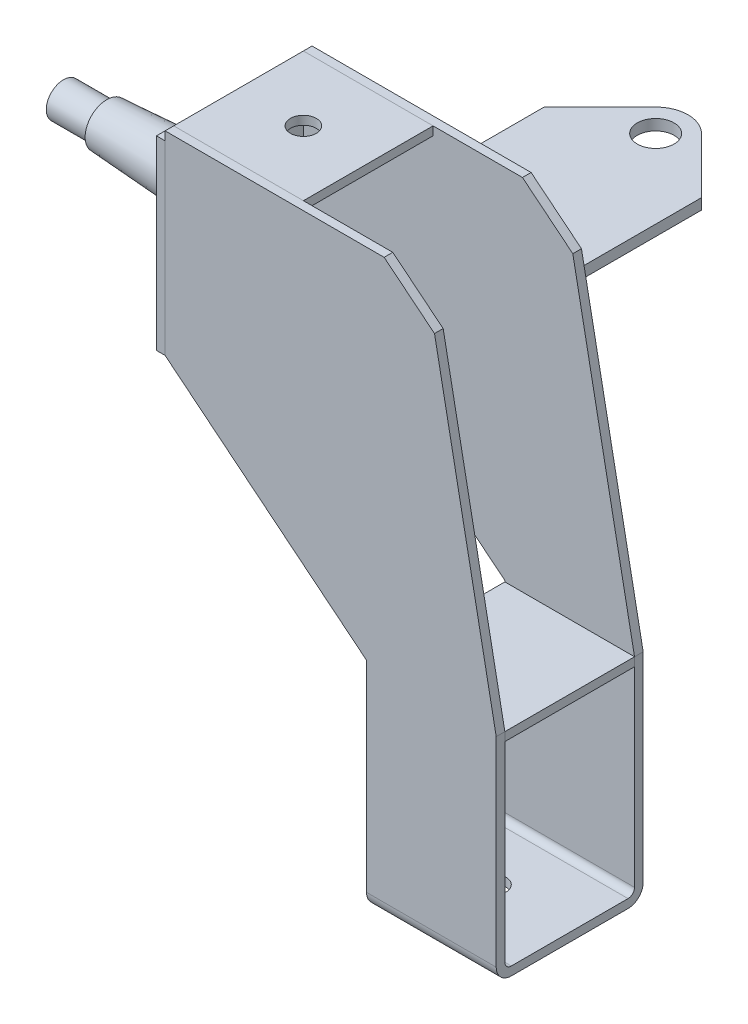
SolidWorks part; units mm, degrees
ref_plane "Front Plane" through (0, 0, 0) normal (0, 0, 1) x (1, 0, 0)
ref_plane "Top Plane" through (0, 0, 0) normal (0, 1, 0) x (1, 0, 0)
ref_plane "Right Plane" through (0, 0, 0) normal (1, 0, 0) x (0, 0, -1)
sketch "Sketch1" plane through (0, 0, 0) normal (0, 0, 1) x (1, 0, 0)
  line L0 (0, 0) -> (0, -100)
  line L1 (0, -2.2) -> (0, 2.2) construction
  line L2 (0, 0) -> (93.2275, 75.5556)
  line L3 (93.2275, 75.5556) -> (93.2275, 165.5556)
  line L4 (0, -100) -> (-60, -100)
  line L5 (-60, -100) -> (-60, -0.5906)
  line L6 (-60, -0.5906) -> (-31.4466, 146.6667)
  line L7 (-31.4466, 146.6667) -> (-8.1397, 165.5556)
  line L8 (-8.1397, 165.5556) -> (93.2275, 165.5556)
  point P0 (0, 0)
  dimension "D1" = 100
  dimension "D2" = 120
  dimension "D3" = 90
  dimension "D4" = 60
  dimension "D5" = 90
  dimension "D6" = 30
  dimension "D7" = 150
  dimension "D8" = 150
  dimension "D9" = 190
  dimension "D10" = 101.3672
  dimension "D11" = 129.023
  dimension "D12" = 99.4094
sketch "Sketch3" plane through (0, 0, 0) normal (1, 0, 0) x (0, 0, -1)
  line L2 (93.1124, 165.5556) -> (89.1124, 165.5556)
  line L3 (89.1124, 165.5556) -> (89.1124, -93)
  line L4 (86.1124, -96) -> (32.1124, -96)
  line L5 (0, 146.6667) -> (0, 165.5556) construction
  line L6 (0, 75.5556) -> (0, 165.5556) construction
  line L7 (0, -100) -> (0, -0.5906) construction
  line L8 (0, 84.2751) -> (0, -84.2751) construction
  line L9 (29.1124, -93) -> (29.1124, 165.5556)
  line L10 (29.1124, 165.5556) -> (25.1124, 165.5556)
  line L12 (93.1124, 161.5556) -> (93.1124, 161.5556)
  line L13 (93.1124, 165.5556) -> (93.1124, -93)
  line L14 (86.1124, -100) -> (32.1124, -100)
  line L15 (25.1124, -93) -> (25.1124, 168.1451)
  line L16 (25.1124, 161.5556) -> (25.1124, 161.5556)
  line L17 (93.1124, 161.5556) -> (93.1124, -93) construction
  line L18 (25.1124, -93) -> (25.1124, 161.5556) construction
  arc A0 (32.1124, -96) -> (29.1124, -93) centre (32.1124, -93) cw
  arc A1 (89.1124, -93) -> (86.1124, -96) centre (86.1124, -93) cw
  arc A2 (93.1124, -93) -> (86.1124, -100) centre (86.1124, -93) cw
  arc A3 (32.1124, -100) -> (25.1124, -93) centre (32.1124, -93) cw
  point P2 (0, 165.5556)
  point P7 (0, -100)
  point P20 (29.1124, -96)
  point P23 (89.1124, -96)
  dimension "D6" = 3
  dimension "D1" = 4
  dimension "D5" = 60
extrude "Boss-Extrude2" add sketch "Sketch3" along normal mid plane 214 contours A3 L14 A2 L13 L2 L3 A1 L4 A0 L9 L10 L15
sketch "Sketch4" plane through (0, 0, 0) normal (0, 0, 1) x (1, 0, 0)
  line L8 (-190, 11.8967) -> (-190, -230)
  line L9 (-190, -230) -> (130, -230)
  line L10 (130, -230) -> (130, -61.9751)
  line L11 (130, -61.9751) -> (223.2275, 13.5805)
  line L12 (223.2275, 13.5805) -> (223.2275, 295.5556)
  line L13 (223.2275, 295.5556) -> (-54.2043, 295.5556)
  line L14 (-54.2043, 295.5556) -> (-150.0618, 217.8685)
  line L15 (-150.0618, 217.8685) -> (-190, 11.8967)
  line L16 (-60, -0.5906) -> (-60, -100)
  line L17 (-60, -100) -> (0, -100)
  line L18 (0, -100) -> (0, 0)
  line L19 (0, 0) -> (93.2275, 75.5556)
  line L20 (93.2275, 75.5556) -> (93.2275, 165.5556)
  line L21 (93.2275, 165.5556) -> (-8.1397, 165.5556)
  line L22 (-8.1397, 165.5556) -> (-31.4466, 146.6667)
  line L23 (-31.4466, 146.6667) -> (-60, -0.5906)
  line L24 (-60, -0.5906) -> (-60, -100)
  line L25 (-60, -100) -> (0, -100)
  line L26 (0, -100) -> (0, 0)
  line L27 (0, 0) -> (93.2275, 75.5556)
  line L28 (93.2275, 75.5556) -> (93.2275, 165.5556)
  line L29 (93.2275, 165.5556) -> (-8.1397, 165.5556)
  line L30 (-8.1397, 165.5556) -> (-31.4466, 146.6667)
  line L31 (-31.4466, 146.6667) -> (-60, -0.5906)
  dimension "D1" = 0
  dimension "D2" = 130
extrude "Cut-Extrude1" cut sketch "Sketch4" against normal blind 214
sketch "Sketch5" plane through (0, 0, 0) normal (1, 0, 0) x (0, 0, -1)
  line L0 (89.1124, 0) -> (89.1124, -93) construction
  line L1 (29.1124, -0.5906) -> (89.1124, -0.5906)
  line L2 (29.1124, -0.5906) -> (29.1124, -4.5906)
  line L3 (29.1124, -4.5906) -> (89.1124, -4.5906)
  line L4 (89.1124, -0.5906) -> (89.1124, -4.5906)
  dimension "D1" = 4
  dimension "D2" = 60
extrude "Boss-Extrude3" add sketch "Sketch5" against normal blind 60 separate body
sketch "Sketch6" plane through (93.2275, 0, 0) normal (1, 0, 0) x (0, 0, -1)
  line L0 (89.1124, 165.5556) -> (89.1124, 75.5556) construction
  line L1 (29.1124, 165.5556) -> (89.1124, 165.5556)
  line L2 (29.1124, 165.5556) -> (29.1124, 161.5556)
  line L3 (29.1124, 161.5556) -> (89.1124, 161.5556)
  line L4 (89.1124, 165.5556) -> (89.1124, 161.5556)
  dimension "D1" = 4
extrude "Boss-Extrude4" add sketch "Sketch6" against normal blind 60 separate body
sketch "Sketch7" plane through (93.2275, 0, 0) normal (1, 0, 0) x (0, 0, -1)
  line L0 (25.1124, 161.5556) -> (93.1124, 161.5556)
  line L2 (25.1124, 161.5556) -> (25.1124, 75.5556)
  line L3 (25.1124, 75.5556) -> (26.2037, 75.5556)
  line L4 (93.1124, 161.5556) -> (93.1124, 75.5556)
  line L5 (29.1124, 0) -> (29.1124, 75.5556) construction
  line L6 (89.1124, 75.5556) -> (89.1124, 0) construction
  line L7 (29.1124, 75.5556) -> (29.1124, 165.5556) construction
  line L8 (89.1124, 165.5556) -> (89.1124, 75.5556) construction
  line L9 (48.0211, 75.5556) -> (70.2037, 75.5556)
  line L10 (92.0211, 75.5556) -> (93.1124, 75.5556)
  arc A0 (74.749, 72.6389) -> (87.4758, 72.6389) centre (81.1124, 75.5556) ccw
  arc A1 (30.749, 72.6389) -> (43.4758, 72.6389) centre (37.1124, 75.5556) ccw
  circle A2 centre (37.1124, 155.0821) radius 3
  circle A3 centre (81.1124, 155.0821) radius 3
  arc A4 (30.749, 72.6389) -> (26.2037, 75.5556) centre (26.2037, 70.5556) ccw
  arc A5 (43.4758, 72.6389) -> (48.0211, 75.5556) centre (48.0211, 70.5556) cw
  arc A6 (74.749, 72.6389) -> (70.2037, 75.5556) centre (70.2037, 70.5556) ccw
  arc A7 (87.4758, 72.6389) -> (92.0211, 75.5556) centre (92.0211, 70.5556) cw
  circle A8 centre (37.1124, 75.5556) radius 3
  circle A9 centre (81.1124, 75.5556) radius 3
  point P28 (44.1124, 75.5556)
  point P33 (88.1124, 75.5556)
  dimension "D1" = 14
  dimension "D2" = 14
  dimension "D3" = 6
  dimension "D4" = 6
  dimension "D5" = 8
  dimension "D6" = 8
  dimension "D7" = 79.5266
  dimension "D8" = 8
  dimension "D9" = 8
  dimension "D10" = 44
  dimension "D11" = 5
  dimension "D12" = 5
  dimension "D13" = 5
  dimension "D14" = 5
  dimension "D15" = 6
  dimension "D16" = 6
extrude "Boss-Extrude5" add sketch "Sketch7" along normal blind 4 separate body
sketch "Sketch8" plane through (0, 0, -93.1124) normal (0, 0, -1) x (-1, 0, 0)
  line L1 (12.1021, 115) -> (-60.6218, 115)
  line L2 (12.1021, 115) -> (12.1021, 120)
  line L3 (12.1021, 120) -> (-60.6218, 120)
  line L4 (-60.6218, 115) -> (-60.6218, 120)
  line L5 (12.1021, 117.5) -> (37.1021, 117.5)
  line L7 (60, -0.5906) -> (31.4466, 146.6667) construction
  point P8 (60, -0.5906)
  dimension "D1" = 5
  dimension "D2" = 115
  dimension "D3" = 130
  dimension "D4" = 167.0653
  dimension "D5" = 115.635
  dimension "D6" = 25
extrude "Boss-Extrude6" add sketch "Sketch8" along normal blind 100 separate body contours L4 L1 L2 L3
chamfer "Chamfer1" distance 25 angle 45 1 edges at (-12.1021, 117.5, -193.1124)
chamfer "Chamfer2" distance 25 angle 45 1 edges at (60.6218, 117.5, -193.1124)
sketch "Sketch9" plane through (0, 115, 0) normal (0, -1, 0) x (1, 0, 0)
  line L2 (93.2275, -93.1124) -> (0, -93.1124) construction
  line L3 (60.6218, -168.1124) -> (60.6218, -93.1124) construction
  circle A1 centre (24.2218, -183.1124) radius 15
  dimension "D1" = 30
  dimension "D3" = 36.4
  dimension "D2" = 90
extrude "Boss-Extrude7" add sketch "Sketch9" against normal blind 5
sketch "Sketch10" plane through (97.2275, 0, 0) normal (1, 0, 0) x (0, 0, -1)
  line L0 (25.1124, 165.5556) -> (93.1124, 75.5556)
  circle A0 centre (59.1124, 120.5556) radius 12.25
  dimension "D1" = 24.5
extrude "Cut-Extrude2" cut sketch "Sketch10" against normal blind 4
sketch "Sketch12" plane through (0, 165.5556, 0) normal (0, 1, 0) x (1, 0, 0)
  line L0 (33.2275, 89.1124) -> (93.2275, 29.1124)
  circle A0 centre (63.2275, 59.1124) radius 6
  dimension "D1" = 12
extrude "Cut-Extrude5" cut sketch "Sketch12" against normal blind 8 contours L0 A0 | L0 A0
sketch "Sketch13" plane through (0, -100, 0) normal (0, -1, 0) x (1, 0, 0)
  circle A0 centre (-23.1606, -60.4397) radius 6
extrude "Cut-Extrude6" cut sketch "Sketch13" against normal blind 10
sketch "Sketch15" plane through (93.2275, 0, 0) normal (-1, 0, 0) x (0, 0, 1)
  circle A0 centre (-59.1124, 120.5556) radius 15
  dimension "D1" = 30
extrude "Boss-Extrude8" add sketch "Sketch15" along normal blind 10 separate body
sketch "Sketch16" plane through (97.2275, 0, 0) normal (1, 0, 0) x (0, 0, -1)
  circle A0 centre (59.1124, 120.5556) radius 12.25
extrude "Boss-Extrude9" add sketch "Sketch16" against normal blind 10 separate body
sketch "Sketch17" plane through (97.2275, 0, 0) normal (1, 0, 0) x (0, 0, -1)
  circle A0 centre (59.1124, 120.5556) radius 12.5
  dimension "D1" = 25
extrude "Boss-Extrude10" add sketch "Sketch17" along normal blind 77 separate body
sketch "Sketch18" plane through (174.2275, 0, 0) normal (1, 0, 0) x (0, 0, -1)
  circle A0 centre (59.1124, 120.5556) radius 8
  circle A1 centre (59.1124, 120.5556) radius 12.5
  dimension "D1" = 16
  dimension "D2" = 25
extrude "Cut-Extrude7" cut sketch "Sketch18" against normal blind 20
chamfer "Chamfer3" distance 40 distance2 2.5 1 edges at (154.2275, 120.5556, -71.6124)
combine bodies "Combine1" operation type add bodies to combine 116 114 113
sketch "Sketch19" plane through (0, 115, 0) normal (0, -1, 0) x (1, 0, 0)
  circle A0 centre (24.2218, -183.1124) radius 8.5
  dimension "D1" = 17
extrude "Cut-Extrude8" cut sketch "Sketch19" against normal blind 20
ref_plane "Plane1" through (-100, 0, 0) normal (1, 0, 0) x (0, 0, -1)
mirror "Mirror1" about plane through (-100, 0, 0) normal (1, 0, 0) of bodies 111 112 104 117 118 109
delete or keep bodies "Body-Delete/Keep 1" type delete bodies bodies 104 118 117 112 111 109
